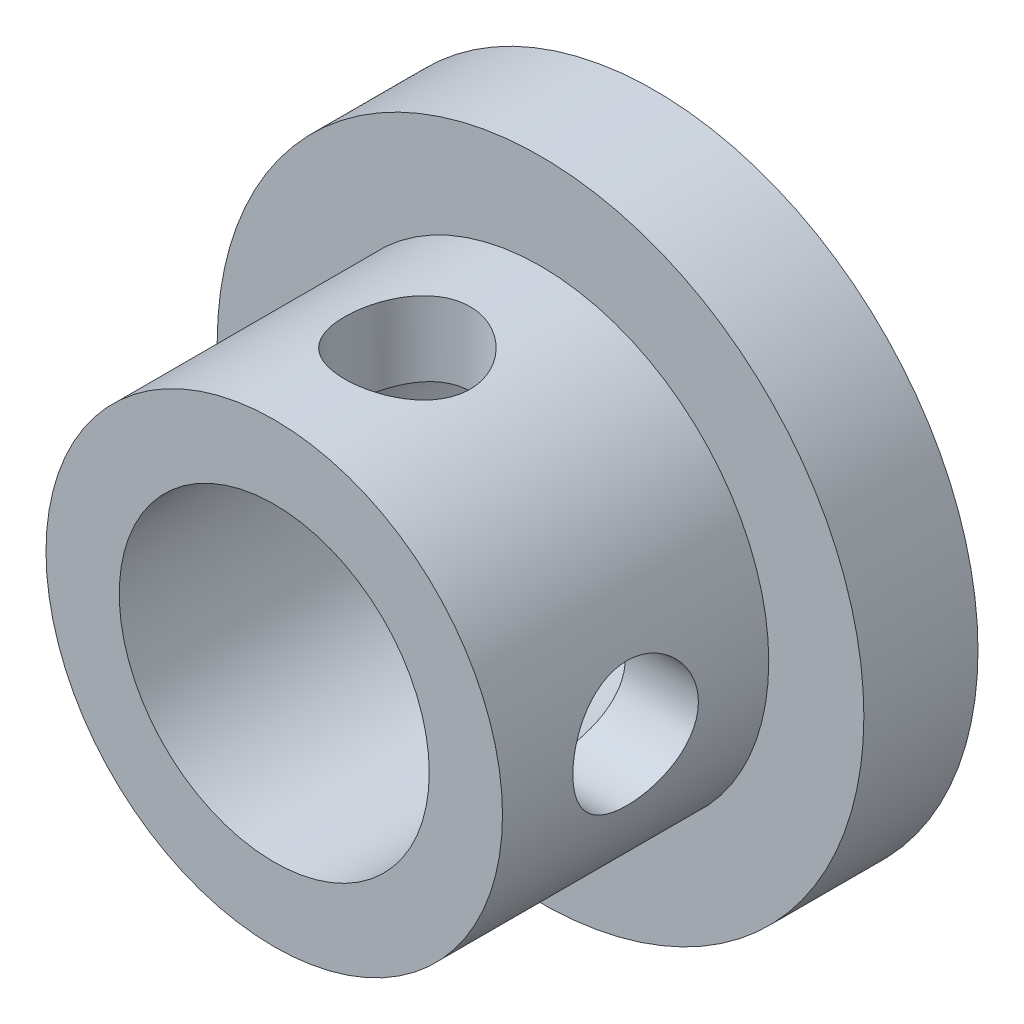
SolidWorks part; units mm, degrees
ref_plane "정면" through (0, 0, 0) normal (0, 0, 1) x (1, 0, 0)
ref_plane "윗면" through (0, 0, 0) normal (0, 1, 0) x (1, 0, 0)
ref_plane "우측면" through (0, 0, 0) normal (1, 0, 0) x (0, 0, -1)
sketch "스케치2" plane through (0, 0, 0) normal (0, 0, 1) x (1, 0, 0)
  circle A0 centre (0, 0) radius 8.5
extrude "보스-돌출2" add sketch "스케치2" along normal blind 3
sketch "스케치3" plane through (0, 0, 3) normal (0, 0, 1) x (1, 0, 0)
  circle A0 centre (0, 0) radius 6
extrude "보스-돌출3" add sketch "스케치3" along normal blind 7
sketch "스케치4" plane through (0, 0, 10) normal (0, 0, 1) x (1, 0, 0)
  circle A0 centre (0, 0) radius 4.075
  dimension "D1" = 8.15
extrude "컷-돌출1" cut sketch "스케치4" against normal through all
sketch "스케치5" plane through (0, 0, 10) normal (0, 0, 1) x (1, 0, 0)
  line L0 (0, 0) -> (0, 6) construction
  line L1 (0, 6) -> (0, 0) construction
  line L2 (0, 0) -> (6, 0) construction
  circle A0 centre (0, 0) radius 6 construction
hole_wizard "M4 나사 구멍3" positions "3D스케치3" profile "스케치8" tap size "M4" standard "KS"
sketch3d "3D스케치3"
  point P0 (0, 6, 6.5)
  point P2 (6, 0, 6.5)
  point P6 (0, 0, 0)
  point P7 (0, 0, 0)
  dimension "D1" = 3.5
  dimension "D2" = 3.5
sketch "스케치8" plane through (0, 6, 6.5) normal (1, 0, 0) x (0, 0, 1)
  line L0 (0, 0) -> (0, 1.925)
  line L1 (0, 1.925) -> (1.65, 1.925)
  line L2 (1.65, 1.925) -> (1.65, 0)
  line L5 (1.65, 0) -> (0, 0)
  line L11 (0, -6.35) -> (0, 107.95) construction
  dimension "관통 탭 드릴 지름" = 3.3
  dimension "관통 탭 드릴 깊이" = 1.925
cosmetic thread "구멍 나사산5" parameters "D2"=4
cosmetic thread "구멍 나사산6" parameters "D2"=4
